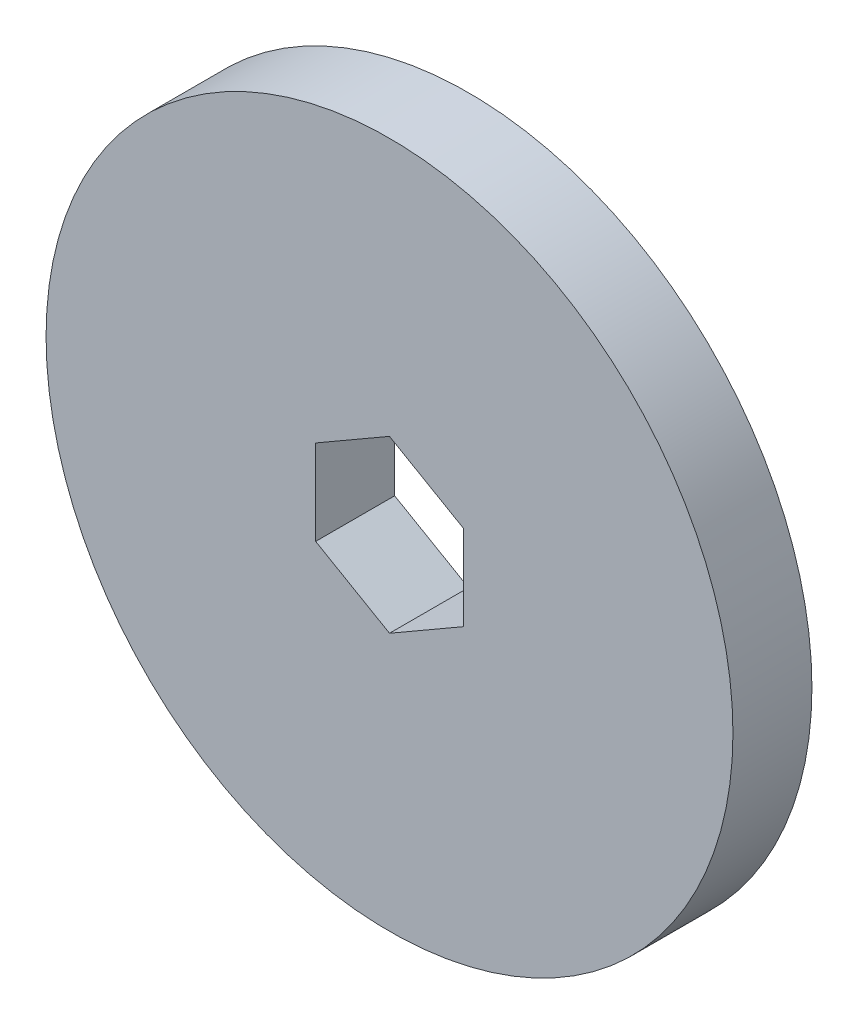
SolidWorks part; units mm, degrees
ref_plane "Front Plane" through (0, 0, 0) normal (0, 0, 1) x (1, 0, 0)
ref_plane "Top Plane" through (0, 0, 0) normal (0, 1, 0) x (1, 0, 0)
ref_plane "Right Plane" through (0, 0, 0) normal (1, 0, 0) x (0, 0, -1)
sketch "Sketch1" plane through (0, 0, 0) normal (0, 0, 1) x (1, 0, 0)
  line L1 (0, -6.3058) -> (5.461, -3.1529)
  line L2 (5.461, -3.1529) -> (5.461, 3.1529)
  line L3 (5.461, 3.1529) -> (0, 6.3058)
  line L4 (0, 6.3058) -> (-5.461, 3.1529)
  line L5 (-5.461, 3.1529) -> (-5.461, -3.1529)
  line L6 (-5.461, -3.1529) -> (0, -6.3058)
  circle A0 centre (0, 0) radius 5.461 construction
  circle A1 centre (0, 0) radius 25.4
  dimension "D2" = 50.8
  dimension "D1" = 10.922
extrude "Boss-Extrude1" add sketch "Sketch1" along normal blind 5.842
